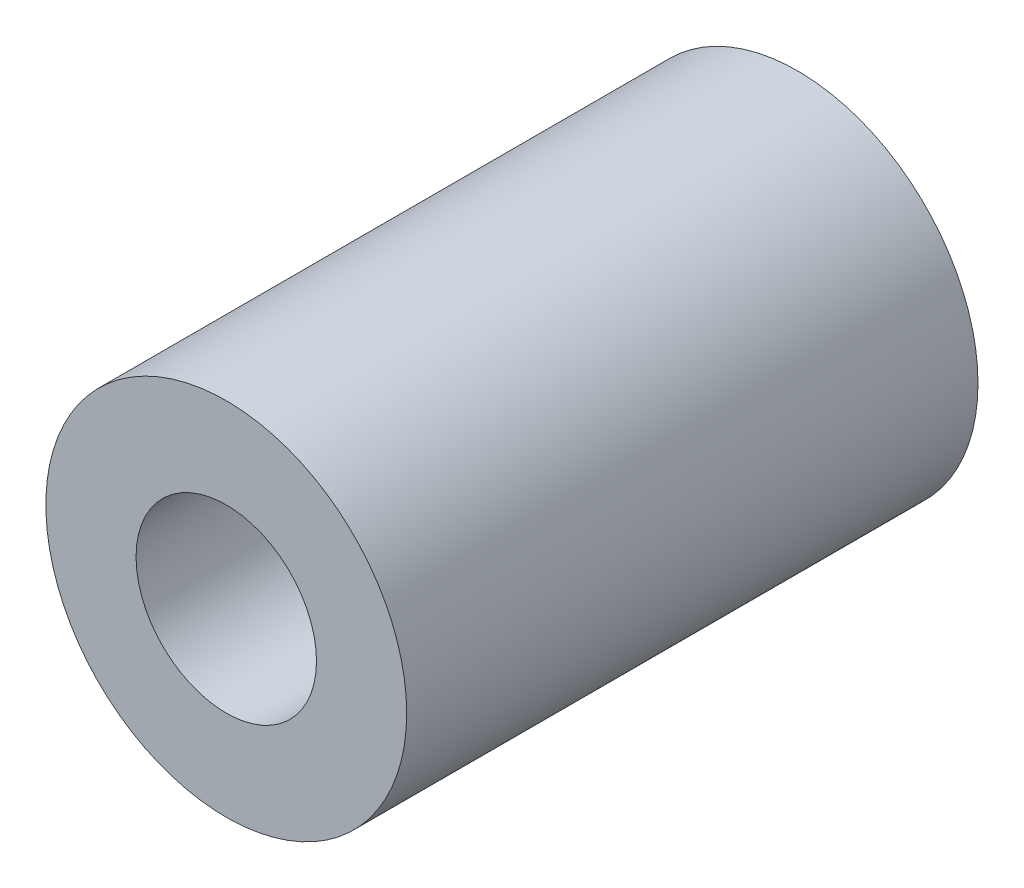
SolidWorks part; units mm, degrees
material "不锈钢 (铁素体)"
ref_plane "前视基准面" through (0, 0, 0) normal (0, 0, 1) x (1, 0, 0)
ref_plane "上视基准面" through (0, 0, 0) normal (0, 1, 0) x (1, 0, 0)
ref_plane "右视基准面" through (0, 0, 0) normal (1, 0, 0) x (0, 0, -1)
sketch "草图1" plane through (0, 0, 0) normal (0, 0, 1) x (1, 0, 0)
  circle A0 centre (0, 0) radius 3
  circle A1 centre (0, 0) radius 6
  dimension "D1" = 6
  dimension "D2" = 12
extrude "凸台-拉伸1" add sketch "草图1" along normal blind 19
sketch "草图2" plane through (0, 0, 0) normal (0, 0, -1) x (-1, 0, 0)
  line L0 (-6.9829, 4) -> (6.9028, 4) construction
  line L1 (-4.4721, 4) -> (0, 0) construction
  line L2 (0, 0) -> (4.4721, 4) construction
  circle A0 centre (0, 0) radius 6 construction
  dimension "D1" = 4
  dimension "D2" = 8.9443
